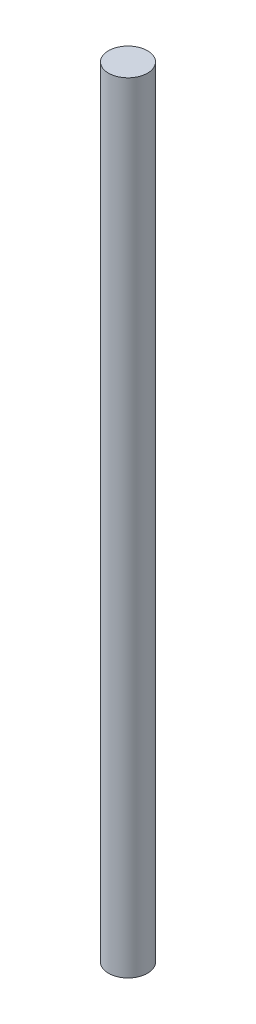
SolidWorks part; units mm, degrees
ref_plane "Front Plane" through (0, 0, 0) normal (0, 0, 1) x (1, 0, 0)
ref_plane "Top Plane" through (0, 0, 0) normal (0, 1, 0) x (1, 0, 0)
ref_plane "Right Plane" through (0, 0, 0) normal (1, 0, 0) x (0, 0, -1)
sketch "Sketch1" plane through (0, 0, 0) normal (0, 1, 0) x (1, 0, 0)
  circle A0 centre (0, 0) radius 1.5875
extrude "Boss-Extrude1" add sketch "Sketch1" along normal blind 63.5
